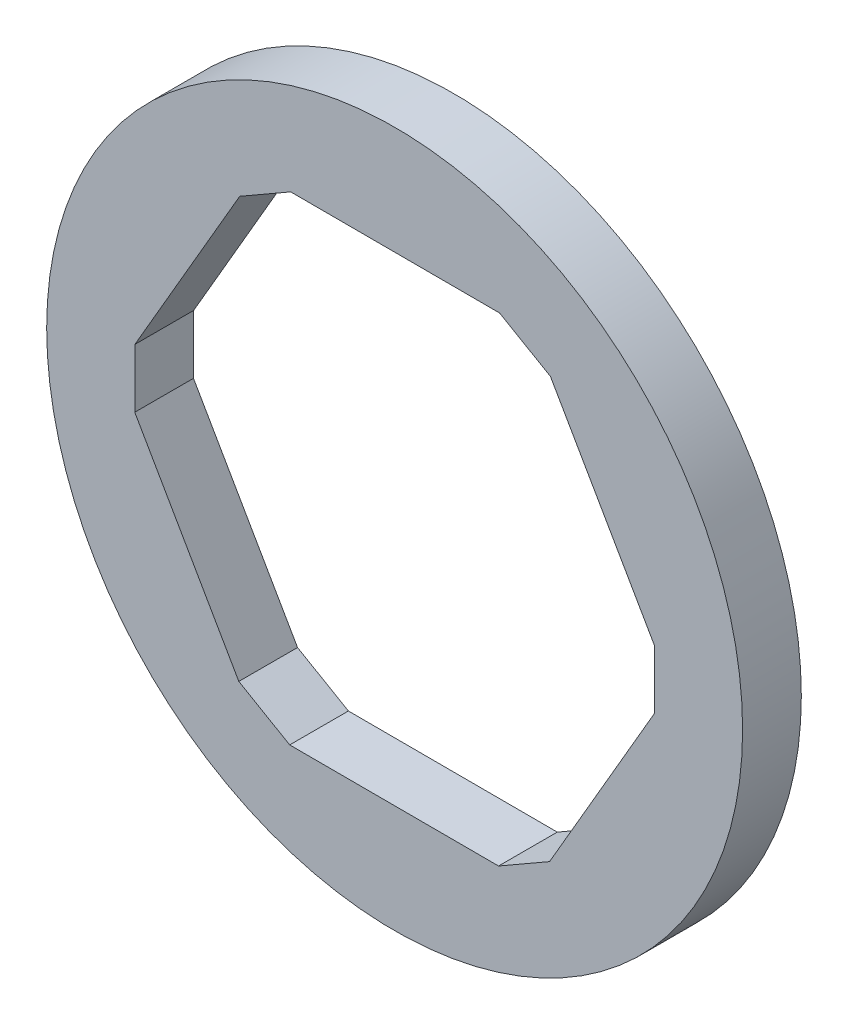
SolidWorks part; units mm, degrees
ref_plane "Front Plane" through (0, 0, 0) normal (0, 0, 1) x (1, 0, 0)
ref_plane "Top Plane" through (0, 0, 0) normal (0, 1, 0) x (1, 0, 0)
ref_plane "Right Plane" through (0, 0, 0) normal (1, 0, 0) x (0, 0, -1)
sketch "Sketch1" plane through (0, 0, 0) normal (0, 0, 1) x (1, 0, 0)
  line L0 (-2.7674, 6.3894) -> (-4.1256, 5.6092)
  line L1 (2.7949, 6.3775) -> (-2.7674, 6.3894)
  line L2 (-4.1256, 5.6092) -> (-6.9171, 0.7981)
  line L3 (-6.9205, -0.7683) -> (-4.1497, -5.5914)
  line L4 (-2.7949, -6.3775) -> (2.7674, -6.3894)
  line L5 (4.1256, -5.6092) -> (6.9171, -0.7981)
  line L6 (6.9205, 0.7683) -> (4.1497, 5.5914)
  line L7 (4.1497, 5.5914) -> (2.7949, 6.3775)
  line L8 (6.9171, -0.7981) -> (6.9205, 0.7683)
  line L9 (2.7674, -6.3894) -> (4.1256, -5.6092)
  line L10 (-4.1497, -5.5914) -> (-2.7949, -6.3775)
  line L11 (-6.9171, 0.7981) -> (-6.9205, -0.7683)
  circle A0 centre (0, 0) radius 9.2668
  circle A1 centre (0, 0) radius 6.3835 construction
  point P4 (3.6992, 6.3755)
  point P5 (-3.6718, 6.3914)
  point P6 (-7.371, 0.0158)
  point P7 (-3.6992, -6.3755)
  point P8 (3.6718, -6.3914)
  point P9 (7.371, -0.0158)
extrude "Boss-Extrude1" add sketch "Sketch1" along normal blind 1.5636
